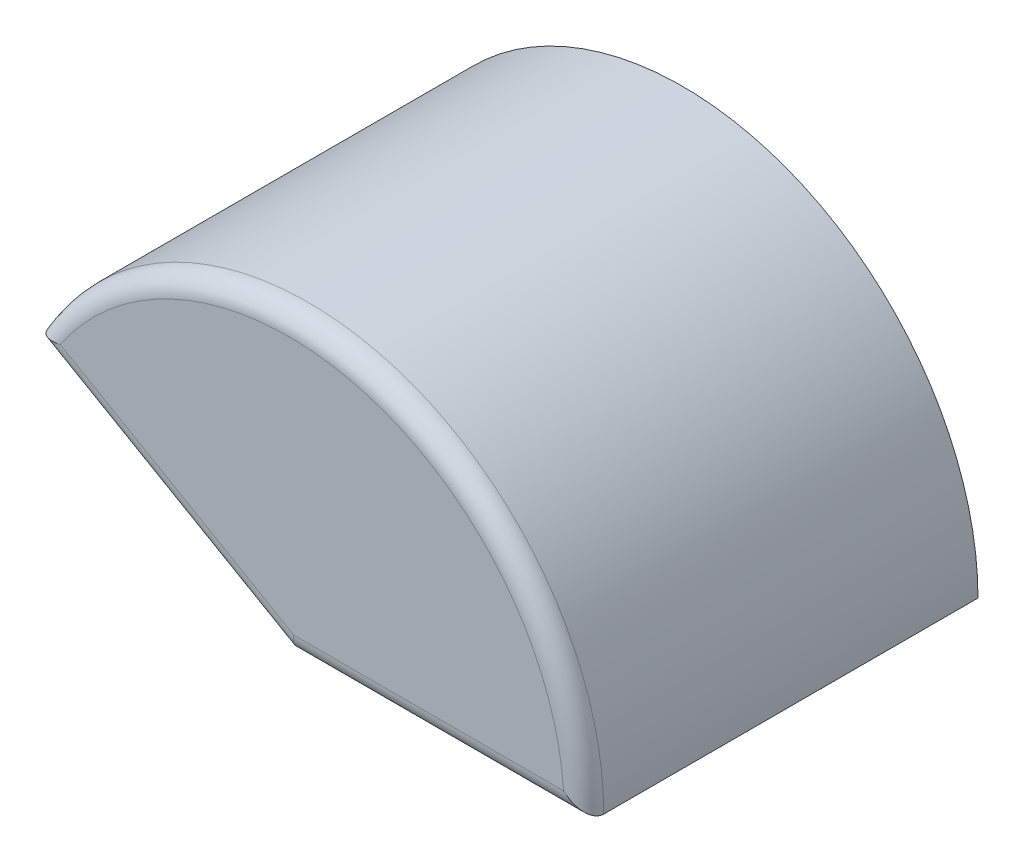
SolidWorks part; units mm, degrees
ref_plane "Front Plane" through (0, 0, 0) normal (0, 0, 1) x (1, 0, 0)
ref_plane "Top Plane" through (0, 0, 0) normal (0, 1, 0) x (1, 0, 0)
ref_plane "Right Plane" through (0, 0, 0) normal (1, 0, 0) x (0, 0, -1)
sketch "Sketch1" plane through (0, 0, 0) normal (0, 0, 1) x (1, 0, 0)
  line L0 (-25.9808, 15) -> (0, 0)
  line L1 (0, 0) -> (30, 0)
  arc A0 (30, 0) -> (-25.9808, 15) centre (0, 0) ccw
  dimension "D1" = 150
  dimension "D2" = 30
extrude "Boss-Extrude1" add sketch "Sketch1" along normal blind 40
fillet "Fillet1" radius 2 3 edges at (-12.9904, 7.5, 40) (7.7646, 28.9778, 40) (15, 0, 40)
equation "\"angle\"=150"
equation "\"thicknes\"=40"
equation "\"diameter\"=30"
equation "\"D1@Sketch1\"= \"angle\""
equation "\"D2@Sketch1\"= \"diameter\""
equation "\"D1@Boss-Extrude1\"= \"thicknes\""
